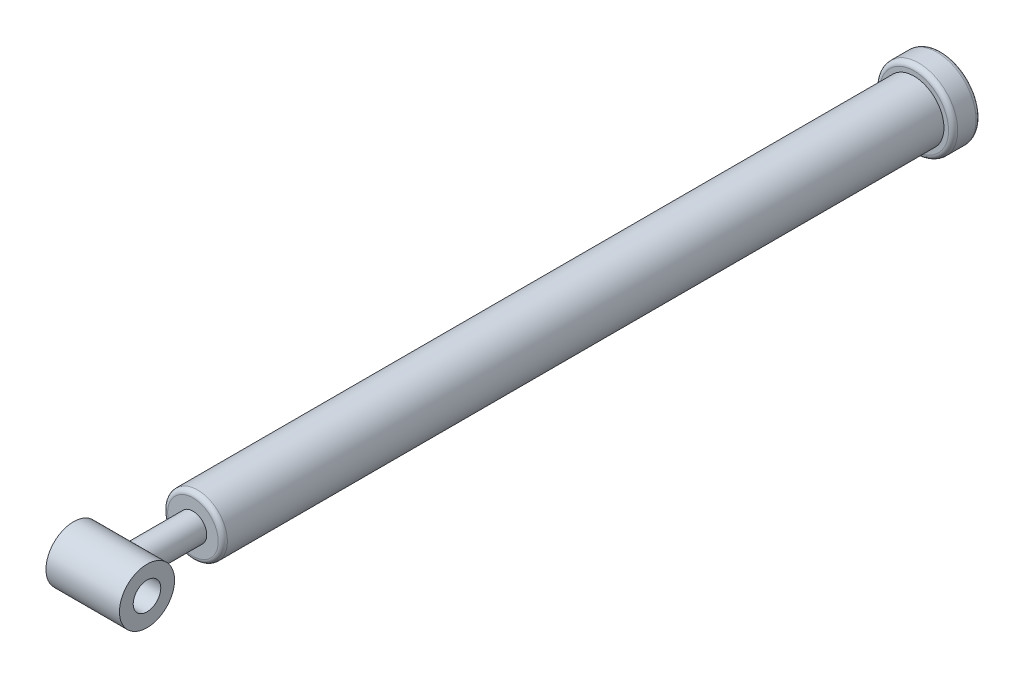
SolidWorks part; units mm, degrees
ref_plane "Front Plane" through (0, 0, 0) normal (0, 0, 1) x (1, 0, 0)
ref_plane "Top Plane" through (0, 0, 0) normal (0, 1, 0) x (1, 0, 0)
ref_plane "Right Plane" through (0, 0, 0) normal (1, 0, 0) x (0, 0, -1)
sketch "Sketch1" plane through (0, 0, 0) normal (0, 0, 1) x (1, 0, 0)
  circle A0 centre (0, 0) radius 42.5
  circle A1 centre (0, 0) radius 20
  dimension "D1" = 85
  dimension "D2" = 40
extrude "Boss-Extrude1" add sketch "Sketch1" against normal blind 30
sketch "Sketch2" plane through (0, 0, 0) normal (0, 0, 1) x (1, 0, 0)
  circle A0 centre (0, 0) radius 32.5
  circle A1 centre (0, 0) radius 20 construction
  circle A2 centre (0, 0) radius 20
  dimension "D1" = 65
extrude "Boss-Extrude2" add sketch "Sketch2" along normal blind 780
sketch "Sketch3" plane through (0, 0, 780) normal (0, 0, 1) x (1, 0, 0)
  circle A0 centre (0, 0) radius 32.5 construction
  circle A1 centre (0, 0) radius 32.5
extrude "Boss-Extrude3" add sketch "Sketch3" along normal blind 5
sketch "Sketch4" plane through (0, 0, 785) normal (0, 0, 1) x (1, 0, 0)
  circle A0 centre (0, 0) radius 15
  dimension "D1" = 30
extrude "Boss-Extrude4" add sketch "Sketch4" along normal blind 65
sketch "Sketch5" plane through (0, 0, 0) normal (1, 0, 0) x (0, 0, -1)
  line L0 (-785, 15) -> (-785, -15) construction
  line L1 (-850, 0) -> (-875, 0) construction
  line L2 (-850, 15) -> (-850, -15) construction
  circle A0 centre (-875, 0) radius 30
  circle A1 centre (-875, 0) radius 15
  dimension "D2" = 30
  dimension "D3" = 60
  dimension "D1" = 90
extrude "Boss-Extrude5" add sketch "Sketch5" along normal mid plane 80
fillet "Fillet1" radius 5 3 edges at (42.5, 0, 0) (42.5, 0, -30) (32.5, 0, 785)
